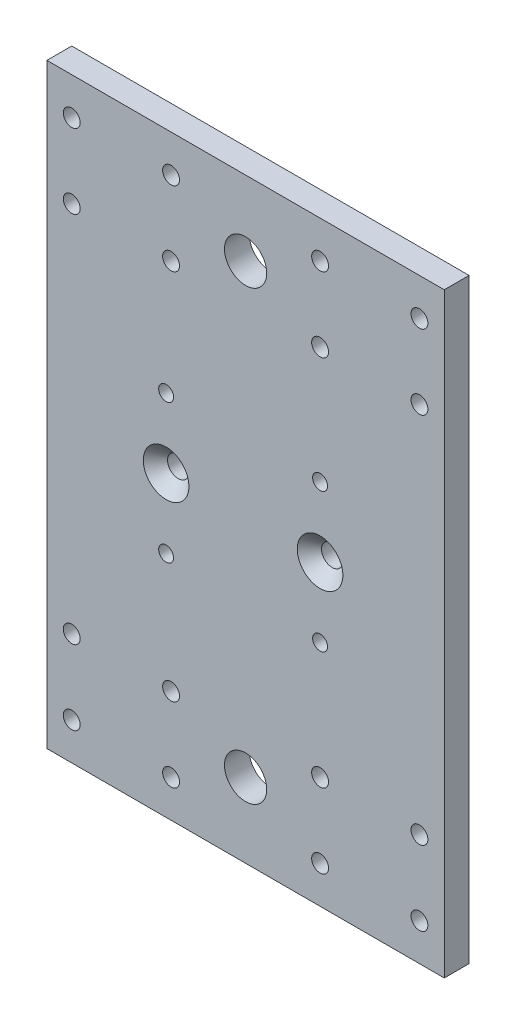
SolidWorks part; units mm, degrees
ref_plane "Front Plane" through (0, 0, 0) normal (0, 0, 1) x (1, 0, 0)
ref_plane "Top Plane" through (0, 0, 0) normal (0, 1, 0) x (1, 0, 0)
ref_plane "Right Plane" through (0, 0, 0) normal (1, 0, 0) x (0, 0, -1)
ref_plane "Ebene1" through (0, 0, 10) normal (0, 0, 1) x (1, 0, 0)
sketch "Skizze1" plane through (0, 0, 10) normal (0, 0, 1) x (1, 0, 0)
  line L0 (-80, 120) -> (0, 120)
  line L1 (-80, 120) -> (-80, 0)
  line L4 (-80, 0) -> (0, 0)
  line L5 (0, 0) -> (0, 120)
  line L6 (-80, 60) -> (0, 60) construction
  dimension "D1" = 120
  dimension "D2" = 80
extrude "Aufsatz-Linear austragen1" add sketch "Skizze1" against normal blind 5
hole_wizard "Formsenkung für M4 Senkschraube mit Innensechskant1" positions "Skizze18" profile "Skizze19" countersink size "M4" standard "DIN"
sketch "Skizze18" plane through (0, 0, 10) normal (0, 0, 1) x (1, 0, 0)
  line L0 (-80, 60) -> (0, 60) construction
  line L3 (0, 0) -> (0, 120) construction
  line L4 (-80, 120) -> (-80, 0) construction
  point P0 (-56, 60)
  point P3 (-25, 60)
  dimension "D1" = 31
  dimension "D2" = 25
sketch "Skizze19" plane through (-56, 60, 10) normal (1, 0, 0) x (0, -1, 0)
  line L0 (0, 0) -> (0, 12.7919)
  line L1 (0, 12.7919) -> (2.15, 11.5)
  line L2 (2.15, 11.5) -> (2.15, 2.44)
  line L3 (2.15, 2.44) -> (4.59, 0)
  line L5 (4.59, 0) -> (0, 0)
  line L6 (-2.15, 2.44) -> (-4.59, 0) construction
  line L10 (0, 12.7919) -> (-2.15, 11.5) construction
  line L11 (0, -6.35) -> (0, 107.95) construction
  dimension "Bohrerdurchmesser" = 4.3
  dimension "Bohrungstiefe" = 11.5
  dimension "Senkdurchmesser (Oben)" = 9.18
  dimension "Senkwinkel (Oben)" = 90
  dimension "Spitzenwinkel" = 118
hole_wizard "Ø3.0mm Stiftloch1" positions "Skizze20" profile "Skizze21" hole size "Ø3.0" standard "DIN"
sketch "Skizze20" plane through (0, 0, 10) normal (0, 0, 1) x (1, 0, 0)
  line L0 (-56, 60) -> (-56, 74) construction
  line L3 (-25, 60) -> (-25, 74) construction
  line L4 (-56, 60) -> (-25, 60) construction
  line L6 (-56, 74) -> (-25, 74) construction
  point P0 (-56, 74)
  point P18 (-25, 74)
  point P26 (-25, 46)
  point P27 (-56, 46)
  dimension "D1" = 28
sketch "Skizze21" plane through (-56, 74, 10) normal (1, 0, 0) x (0, -1, 0)
  line L0 (0, 0) -> (0, 12.4013)
  line L1 (0, 12.4013) -> (1.5, 11.5)
  line L2 (1.5, 11.5) -> (1.5, 0)
  line L5 (1.5, 0) -> (0, 0)
  line L10 (0, 12.4013) -> (-1.5, 11.5) construction
  line L11 (0, -6.35) -> (0, 107.95) construction
  dimension "Bohrerdurchmesser" = 3
  dimension "Bohrungstiefe" = 11.5
  dimension "Spitzenwinkel" = 118
hole_wizard "Stirnsenkung für M3 Flachkopfschraube mit Schlitz2" positions "Skizze24" profile "Skizze25" counterbore size "M3" standard "DIN"
sketch "Skizze24" plane through (0, 0, 5) normal (0, 0, -1) x (-1, 0, 0)
  line L0 (25, 112.5) -> (25, 97.5) construction
  line L1 (0, 120) -> (80, 120) construction
  line L2 (80, 0) -> (0, 0) construction
  line L3 (15, 120) -> (15, 0) construction
  line L7 (80, 60) -> (0, 60) construction
  line L8 (80, 120) -> (80, 0) construction
  line L9 (0, 0) -> (0, 120) construction
  point P0 (25, 112.5)
  point P12 (25, 97.5)
  point P23 (5, 97.5)
  point P24 (5, 112.5)
  point P34 (25, 22.5)
  point P35 (25, 7.5)
  point P36 (5, 7.5)
  point P37 (5, 22.5)
  dimension "D1" = 15
  dimension "D2" = 20
  dimension "D3" = 15
  dimension "D5" = 90
  dimension "D4" = 2
sketch "Skizze25" plane through (-25, 112.5, 5) normal (1, 0, 0) x (0, 1, 0)
  line L0 (0, 0) -> (0, 9.5215)
  line L1 (0, 9.5215) -> (1.7, 8.5)
  line L2 (1.7, 8.5) -> (1.7, 2.4)
  line L3 (1.7, 2.4) -> (3.5, 2.4)
  line L4 (3.5, 2.4) -> (3.5, 0)
  line L5 (3.5, 0) -> (0, 0)
  line L10 (0, 9.5215) -> (-1.7, 8.5) construction
  line L11 (0, -6.35) -> (0, 107.95) construction
  dimension "Bohrerdurchmesser" = 3.4
  dimension "Bohrungstiefe" = 8.5
  dimension "Senkdurchmesser2" = 7
  dimension "Senktiefe2" = 2.4
  dimension "Spitzenwinkel" = 118
hole_wizard "M10 Gewindebohrung1" positions "Skizze26" profile "Skizze27" tap size "M10" standard "DIN" end condition through all
sketch "Skizze26" plane through (0, 0, 5) normal (0, 0, -1) x (-1, 0, 0)
  line L0 (40, 0) -> (40, 120) construction
  line L1 (80, 0) -> (0, 0) construction
  line L2 (0, 120) -> (80, 120) construction
  line L4 (0, 0) -> (0, 120) construction
  line L5 (0, 60) -> (80, 60) construction
  line L6 (80, 120) -> (80, 0) construction
  point P0 (40, 15)
  dimension "D1" = 40
  dimension "D2" = 45
sketch "Skizze27" plane through (-40, 15, 5) normal (1, 0, 0) x (0, 1, 0)
  line L0 (0, 0) -> (0, 5)
  line L1 (0, 5) -> (4.25, 5)
  line L2 (4.25, 5) -> (4.25, 0)
  line L5 (4.25, 0) -> (0, 0)
  line L11 (0, -6.35) -> (0, 107.95) construction
  dimension "Bohrerdurchmesser" = 8.5
  dimension "Bohrungstiefe" = 5
cosmetic thread "Bohrungsgewinde1" parameters "D2"=10
pattern_linear "Lineares Muster1" count 2 spacing 50 along (-1, 0, 0) of "Stirnsenkung für M3 Flachkopfschraube mit Schlitz2"
ref_plane "Ebene2" through (0, 60, 0) normal (0, -1, 0) x (-1, 0, 0)
mirror "Spiegeln1" about plane through (0, 60, 0) normal (0, -1, 0) of "M10 Gewindebohrung1"
